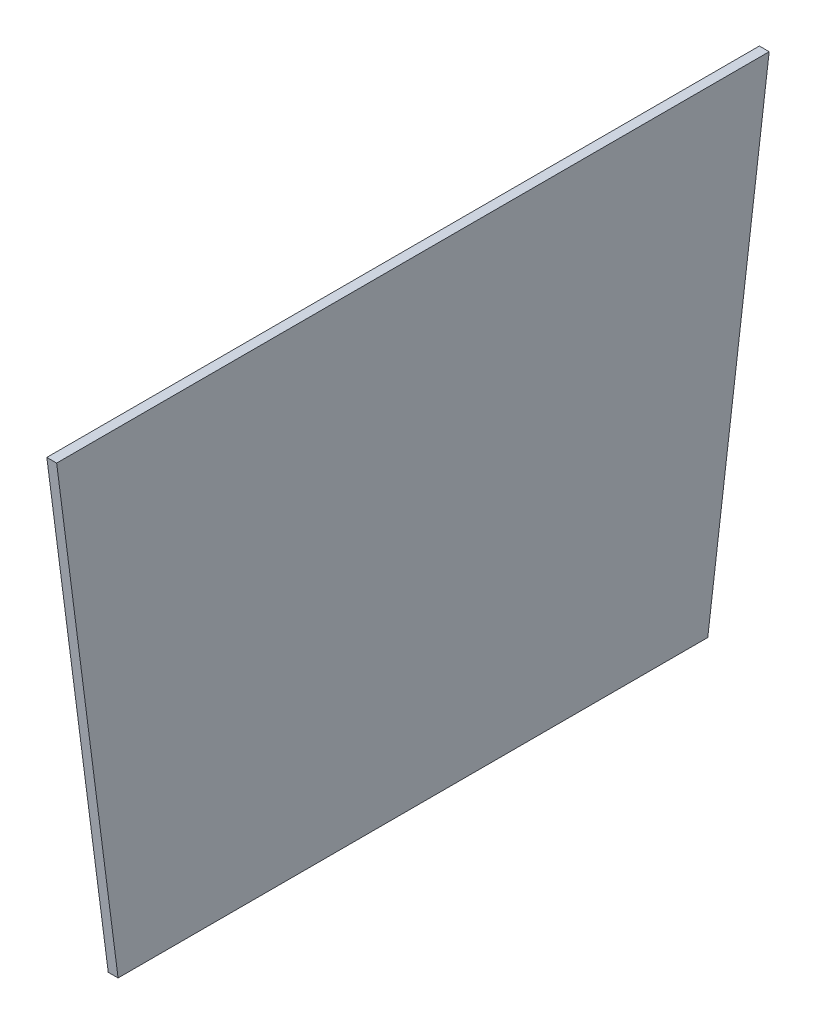
SolidWorks part; units mm, degrees
ref_plane "Front Plane" through (0, 0, 0) normal (0, 0, 1) x (1, 0, 0)
ref_plane "Top Plane" through (0, 0, 0) normal (0, 1, 0) x (1, 0, 0)
ref_plane "Right Plane" through (0, 0, 0) normal (1, 0, 0) x (0, 0, -1)
sketch "Sketch1" plane through (0, 0, 0) normal (1, 0, 0) x (0, 0, -1)
  line L0 (-184.15, 246.38) -> (184.15, 246.38)
  line L1 (184.15, 246.38) -> (152.4, 0)
  line L2 (152.4, 0) -> (-152.4, 0)
  line L3 (-152.4, 0) -> (-184.15, 246.38)
  point P3 (0, 246.38)
  point P8 (0, 0)
  dimension "D1" = 304.8
  dimension "D2" = 368.3
  dimension "D3" = 246.38
extrude "Boss-Extrude1" add sketch "Sketch1" along normal blind 5.08
